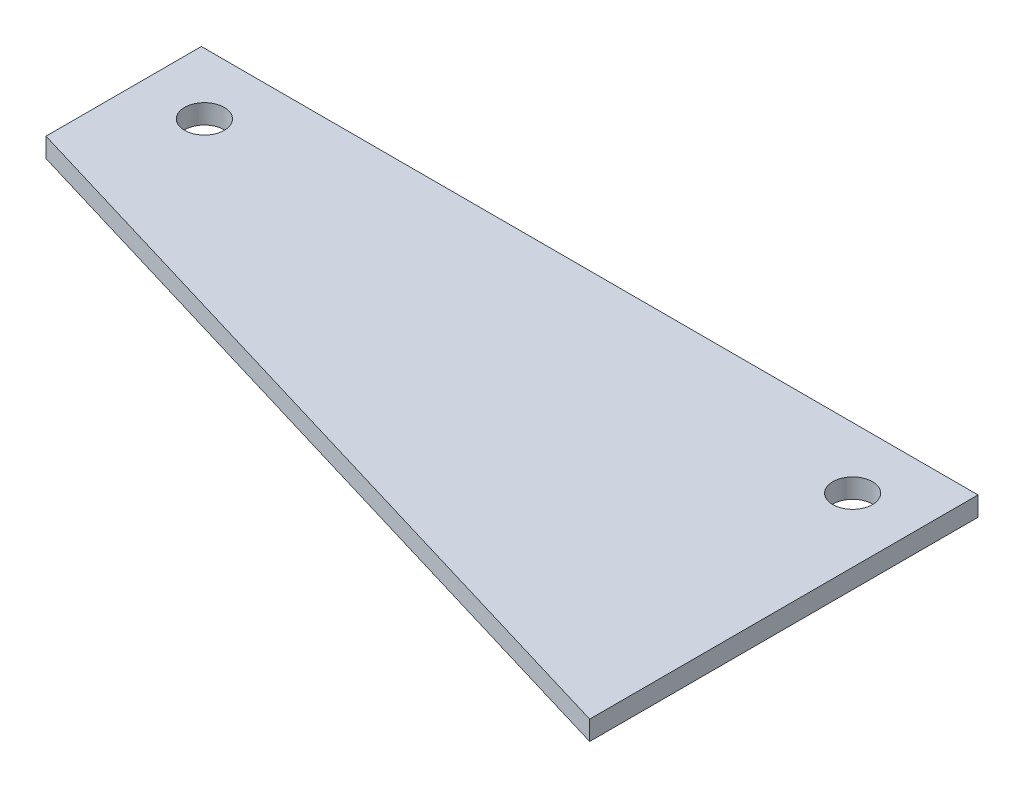
SolidWorks part; units mm, degrees
material "AISI 4130 Steel, annealed at 865C"
ref_plane "X-Y Datum" through (0, 0, 0) normal (0, 0, 1) x (1, 0, 0)
ref_plane "X-Z Datum" through (0, 0, 0) normal (0, 1, 0) x (1, 0, 0)
ref_plane "Y-Z Datum" through (0, 0, 0) normal (1, 0, 0) x (0, 0, -1)
sketch "Sketch1" plane through (0, 0, 0) normal (0, 1, 0) x (1, 0, 0)
  line L1 (-63.5, -38.1) -> (63.5, -38.1)
  line L2 (-63.5, -38.1) -> (-63.5, 38.1)
  line L3 (-63.5, 38.1) -> (63.5, 38.1)
  line L4 (63.5, -38.1) -> (63.5, 38.1)
  line L5 (-63.5, -38.1) -> (63.5, 38.1) construction
  line L6 (-63.5, 38.1) -> (63.5, -38.1) construction
  point P0 (0, 0)
  dimension "D1" = 127
  dimension "D2" = 76.2
extrude "Boss-Extrude1" add sketch "Sketch1" along normal blind 3.175 contours L3 L4 L1 L2
sketch "Sketch2" plane through (0, 3.175, 0) normal (0, 1, 0) x (1, 0, 0)
  line L0 (-63.5, 12.7) -> (63.5, -25.4)
  line L4 (-63.5, 38.1) -> (-63.5, -38.1)
  line L5 (-63.5, -38.1) -> (63.5, -38.1)
  line L6 (63.5, -38.1) -> (63.5, 38.1)
  line L7 (63.5, 38.1) -> (-63.5, 38.1)
  line L8 (-63.5, 38.1) -> (-63.5, -38.1)
  line L9 (-63.5, -38.1) -> (63.5, -38.1)
  line L10 (63.5, -38.1) -> (63.5, 38.1)
  line L11 (63.5, 38.1) -> (-63.5, 38.1)
  circle A0 centre (53, 28.1) radius 3.25 construction
  circle A1 centre (-53, 28.1) radius 3.25 construction
  circle A2 centre (53, 28.1) radius 3.25
  circle A3 centre (-53, 28.1) radius 3.25
  point P6 (0, 0)
  line M5 (-63.5, 38.1) -> (-63.5, -38.1)
  line M6 (-63.5, -38.1) -> (63.5, -38.1)
  line M7 (63.5, -38.1) -> (63.5, 38.1)
  dimension "D2" = 25.4
  dimension "D3" = 63.5
  dimension "D1" = 0
extrude "Cut-Extrude1" cut sketch "Sketch2" against normal through all contours L0 M5 M6 M7 | A3 | A2
